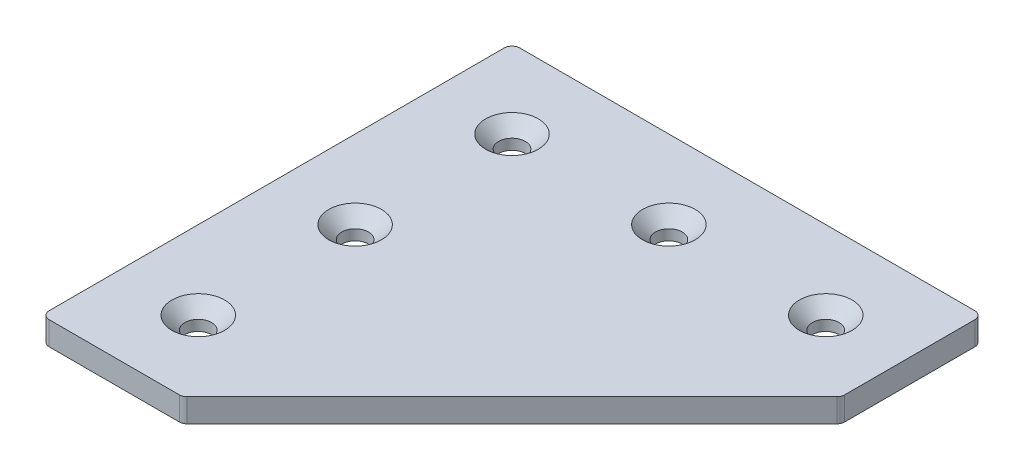
SolidWorks part; units mm, degrees
ref_plane "Front" through (0, 0, 0) normal (0, 0, 1) x (1, 0, 0)
ref_plane "Top" through (0, 0, 0) normal (0, 1, 0) x (1, 0, 0)
ref_plane "Right" through (0, 0, 0) normal (1, 0, 0) x (0, 0, -1)
sketch "Sketch2" plane through (0, 0, 0) normal (0, 1, 0) x (1, 0, 0)
  line L1 (-30, -30) -> (30, -30)
  line L8 (-30, -30) -> (-30, 30)
  line L9 (-30, 30) -> (30, 30)
  line L10 (30, -30) -> (30, 30)
  line L11 (-30, -30) -> (30, 30) construction
  line L12 (-30, 30) -> (30, -30) construction
  point P0 (0, 0)
  dimension "D1" = 60
  dimension "D2" = 60
extrude "Boss-Extrude1" add sketch "Sketch2" along normal blind 3
sketch "Sketch3" plane through (0, 3, 0) normal (0, 1, 0) x (1, 0, 0)
  line L0 (30, 12) -> (-12, -30)
  line L1 (30, -30) -> (30, 30) construction
  line L2 (-30, -30) -> (30, -30) construction
  line L3 (-12, -30) -> (30, -30)
  line L4 (30, -30) -> (30, 12)
  dimension "D1" = 18
  dimension "D2" = 18
extrude "Cut-Extrude1" cut sketch "Sketch3" against normal blind 10
sketch "Sketch4" plane through (0, 3, 0) normal (0, 1, 0) x (1, 0, 0)
  line L0 (-20, -30) -> (-20, 30) construction
  line L2 (30, 30) -> (-30, 30) construction
  line L3 (30, 20) -> (-30, 20) construction
  line L6 (-30, 30) -> (-30, -30) construction
  circle A0 centre (-20, 20) radius 1.75
  circle A1 centre (20, 20) radius 1.75
  circle A2 centre (-20, -20) radius 1.75
  circle A3 centre (-20, 0) radius 1.75
  circle A4 centre (0, 20) radius 1.75
  point P22 (0, 0)
  point P23 (-21.509, 0)
  dimension "D1" = 3.5
  dimension "D2" = 40
  dimension "D3" = 40
  dimension "D4" = 20
  dimension "D5" = 20
  dimension "D6" = 10
  dimension "D7" = 10
hole_wizard "CSK for M3 Hex Socket Countersunk Cap Screw1" positions "3DSketch1" profile "Sketch6" countersink size "M3" standard "ISO" end condition through all
sketch3d "3DSketch1"
  point P0 (-20, 3, -20)
  point P3 (0, 3, -20)
  point P6 (20, 3, -20)
  point P9 (-20, 3, 0)
  point P12 (-20, 3, 20)
sketch "Sketch6" plane through (-20, 3, -20) normal (1, 0, 0) x (0, 0, 1)
  line L0 (0, 0) -> (0, 3)
  line L1 (0, 3) -> (1.7, 3)
  line L2 (1.7, 3) -> (1.7, 1.66)
  line L3 (1.7, 1.66) -> (3.36, 0)
  line L5 (3.36, 0) -> (0, 0)
  line L6 (-1.7, 1.66) -> (-3.36, 0) construction
  line L11 (0, -6.35) -> (0, 107.95) construction
  dimension "Thru Hole Dia." = 3.4
  dimension "Thru Hole Depth" = 3
  dimension "Near C'Sink Dia." = 6.72
  dimension "Near C'Sink Angle" = 90
fillet "Fillet1" radius 1 5 edges at (-30, 1.5, -30) (30, 1.5, -30) (30, 1.5, -12) (-12, 1.5, 30) (-30, 1.5, 30)
